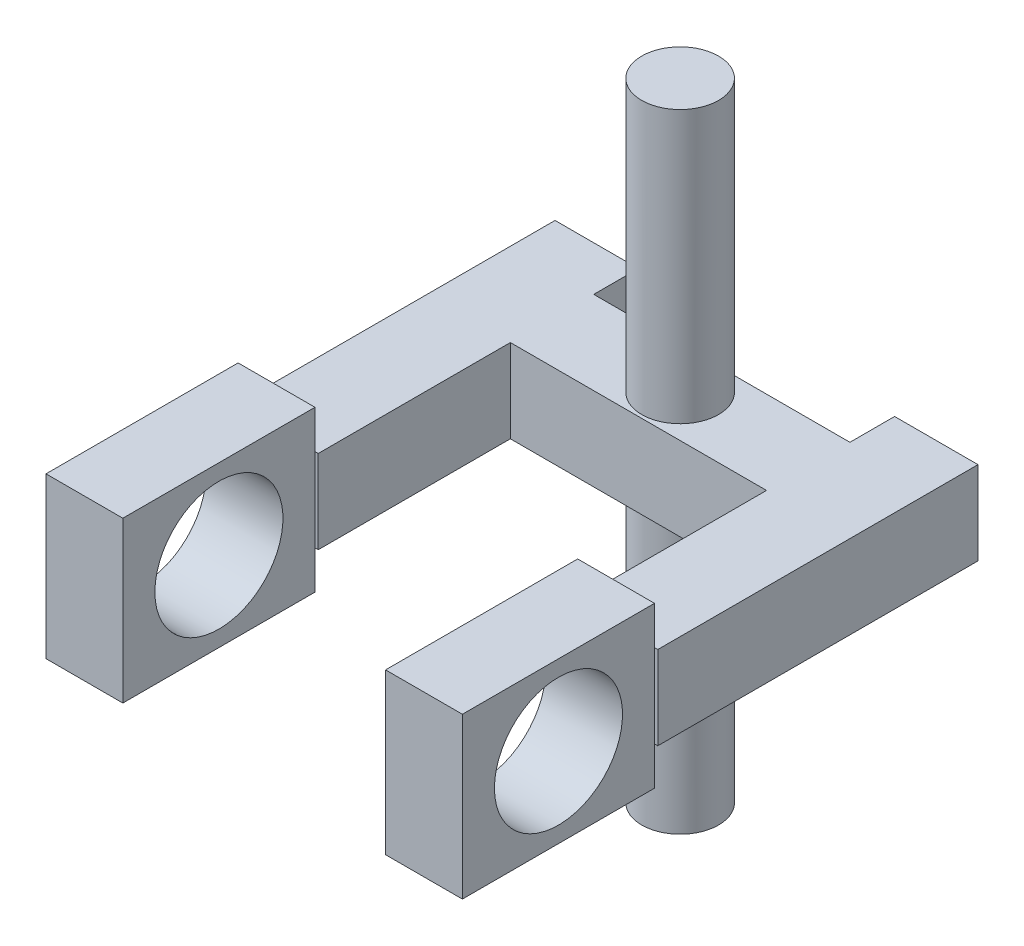
SolidWorks part; units mm, degrees
ref_plane "Front Plane" through (0, 0, 0) normal (0, 0, 1) x (1, 0, 0)
ref_plane "Top Plane" through (0, 0, 0) normal (0, 1, 0) x (1, 0, 0)
ref_plane "Right Plane" through (0, 0, 0) normal (1, 0, 0) x (0, 0, -1)
sketch "Sketch1" plane through (0, 0, 0) normal (0, 1, 0) x (1, 0, 0)
  circle A0 centre (0, 0) radius 6
  dimension "D1" = 12
extrude "Boss-Extrude1" add sketch "Sketch1" along normal blind 98
sketch "Sketch2" plane through (0, 98, 0) normal (0, 1, 0) x (1, 0, 0)
  line L1 (-20, -6.511) -> (20, -6.511)
  line L2 (-20, -6.511) -> (-20, 6.511)
  line L3 (-20, 6.511) -> (20, 6.511)
  line L4 (20, -6.511) -> (20, 6.511)
  line L5 (-20, -6.511) -> (20, 6.511) construction
  line L6 (-20, 6.511) -> (20, -6.511) construction
  point P0 (0, 0)
  dimension "D1" = 40
  dimension "D2" = 13.022
extrude "Boss-Extrude2" add sketch "Sketch2" against normal blind 13.022 from offset 42.489 offset against normal yes
sketch "Sketch4" plane through (0, 0, 6.511) normal (0, 0, 1) x (1, 0, 0)
  line L0 (-20, 42.489) -> (20, 42.489) construction
  line L1 (-20, 55.511) -> (-33.022, 55.511)
  line L2 (-20, 55.511) -> (-20, 42.489)
  line L3 (-20, 42.489) -> (-33.022, 42.489)
  line L4 (-33.022, 55.511) -> (-33.022, 42.489)
  line L5 (20, 55.511) -> (33.022, 55.511)
  line L6 (20, 55.511) -> (20, 42.489)
  line L7 (20, 42.489) -> (33.022, 42.489)
  line L8 (33.022, 55.511) -> (33.022, 42.489)
  dimension "D1" = 13.022
  dimension "D2" = 13.022
extrude "Boss-Extrude3" add sketch "Sketch4" along normal blind 30 and the other way blind 20
sketch "Sketch5" plane through (-33.022, 0, 0) normal (-1, 0, 0) x (0, 0, 1)
  line L0 (36.511, 55.511) -> (36.511, 42.489) construction
  circle A0 centre (21.511, 49) radius 10
  point P6 (36.511, 49)
  dimension "D1" = 20
  dimension "D2" = 15
sketch "Sketch6" plane through (0, 0, 36.511) normal (0, 0, 1) x (1, 0, 0)
  line L0 (-20, 55.511) -> (-33.022, 55.511) construction
  line L1 (-31.962, 43.549) -> (-21.06, 43.549)
  line L2 (-31.962, 43.549) -> (-31.962, 54.451)
  line L3 (-31.962, 54.451) -> (-21.06, 54.451)
  line L4 (-21.06, 43.549) -> (-21.06, 54.451)
  line L5 (-31.962, 43.549) -> (-21.06, 54.451) construction
  line L6 (-31.962, 54.451) -> (-21.06, 43.549) construction
  line L7 (21.06, 43.549) -> (31.962, 43.549)
  line L8 (21.06, 43.549) -> (21.06, 54.451)
  line L9 (21.06, 54.451) -> (31.962, 54.451)
  line L10 (31.962, 43.549) -> (31.962, 54.451)
  line L11 (21.06, 43.549) -> (31.962, 54.451) construction
  line L12 (21.06, 54.451) -> (31.962, 43.549) construction
  line L13 (-33.022, 42.489) -> (-20, 42.489) construction
  line L14 (-20, 42.489) -> (-20, 55.511) construction
  line L15 (-33.022, 59) -> (-33.022, 39) construction
  line L16 (33.022, 42.489) -> (33.022, 55.511) construction
  line L17 (20, 55.511) -> (20, 42.489) construction
  line L18 (20, 42.489) -> (33.022, 42.489) construction
  line L19 (33.022, 55.511) -> (20, 55.511) construction
  point P0 (-26.511, 49)
  point P5 (26.511, 49)
  dimension "D1" = 1.06
  dimension "D2" = 1.06
  dimension "D3" = 1.06
  dimension "D4" = 1.06
  dimension "D5" = 1.06
  dimension "D6" = 1.06
  dimension "D7" = 1.06
  dimension "D8" = 1.06
extrude "Cut-Extrude1" cut sketch "Sketch6" against normal blind 60
sketch "Sketch7" plane through (0, 0, 6.511) normal (0, 0, 1) x (1, 0, 0)
  line L1 (-31.962, 54.451) -> (-21.06, 54.451)
  line L2 (-31.962, 54.451) -> (-31.962, 43.549)
  line L3 (-31.962, 43.549) -> (-21.06, 43.549)
  line L4 (-21.06, 54.451) -> (-21.06, 43.549)
  line L5 (21.06, 54.451) -> (31.962, 54.451)
  line L6 (21.06, 54.451) -> (21.06, 43.549)
  line L7 (21.06, 43.549) -> (31.962, 43.549)
  line L8 (31.962, 54.451) -> (31.962, 43.549)
extrude "Boss-Extrude4" add sketch "Sketch7" along normal blind 20 from offset 10
sketch "Sketch8" plane through (0, 0, 36.511) normal (0, 0, 1) x (1, 0, 0)
  line L0 (-33.022, 55.511) -> (-20, 42.489) construction
  line L1 (-20, 42.489) -> (-20, 55.511) construction
  line L2 (-20, 55.511) -> (-33.022, 42.489) construction
  line L3 (20, 55.511) -> (33.022, 42.489) construction
  line L4 (33.022, 42.489) -> (33.022, 55.511) construction
  line L5 (33.022, 55.511) -> (20, 42.489) construction
  line L7 (-32.511, 36.5) -> (-20.511, 36.5)
  line L8 (-32.511, 36.5) -> (-32.511, 61.5)
  line L9 (-32.511, 61.5) -> (-20.511, 61.5)
  line L10 (-20.511, 36.5) -> (-20.511, 61.5)
  line L11 (-32.511, 36.5) -> (-20.511, 61.5) construction
  line L12 (-32.511, 61.5) -> (-20.511, 36.5) construction
  line L13 (20.511, 36.5) -> (32.511, 36.5)
  line L14 (20.511, 36.5) -> (20.511, 61.5)
  line L15 (20.511, 61.5) -> (32.511, 61.5)
  line L16 (32.511, 36.5) -> (32.511, 61.5)
  line L17 (20.511, 36.5) -> (32.511, 61.5) construction
  line L18 (20.511, 61.5) -> (32.511, 36.5) construction
  point P12 (-26.511, 49)
  point P21 (26.511, 49)
  dimension "D1" = 25
  dimension "D2" = 25
  dimension "D3" = 12
  dimension "D4" = 12
extrude "Boss-Extrude5" add sketch "Sketch8" along normal blind 30
sketch "Sketch9" plane through (-32.511, 0, 0) normal (-1, 0, 0) x (0, 0, 1)
  line L0 (36.511, 61.5) -> (66.511, 36.5) construction
  line L1 (66.511, 36.5) -> (66.511, 61.5) construction
  line L2 (66.511, 61.5) -> (36.511, 36.5) construction
  line L3 (36.511, 36.5) -> (36.511, 61.5) construction
  circle A0 centre (51.511, 49) radius 10
  dimension "D1" = 20
extrude "Cut-Extrude2" cut sketch "Sketch9" against normal blind 100
